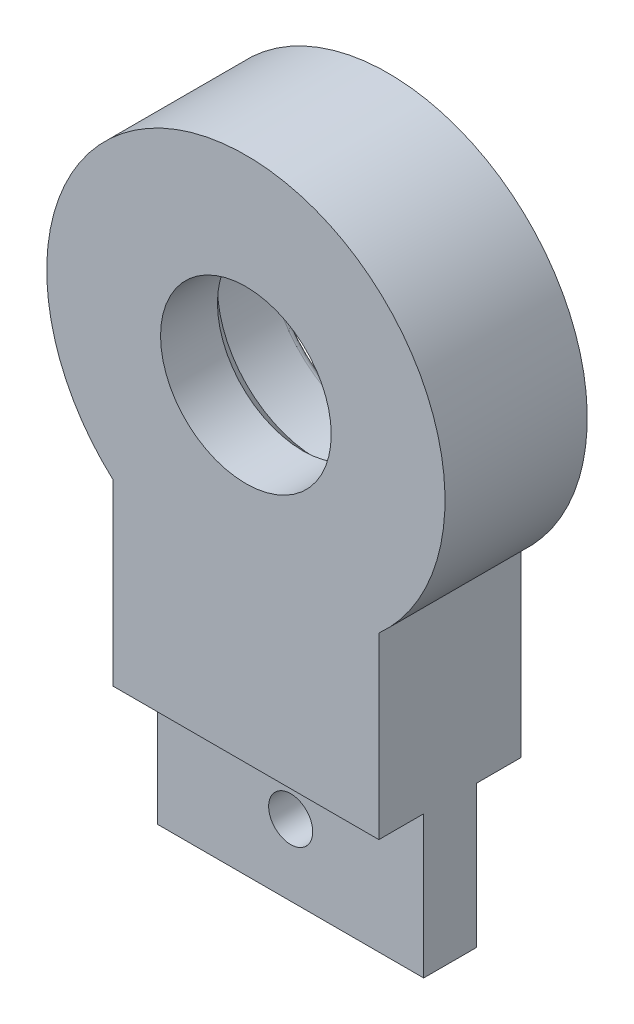
SolidWorks part; units mm, degrees
ref_plane "Front Plane" through (0, 0, 0) normal (0, 0, 1) x (1, 0, 0)
ref_plane "Top Plane" through (0, 0, 0) normal (0, 1, 0) x (1, 0, 0)
ref_plane "Right Plane" through (0, 0, 0) normal (1, 0, 0) x (0, 0, -1)
sketch "Sketch1" plane through (0, 0, 0) normal (0, 0, 1) x (1, 0, 0)
  line L2 (-9.35, -4.9201) -> (-9.35, -17.5)
  line L3 (-9.35, -17.5) -> (9.35, -17.5)
  line L4 (9.35, -4.9201) -> (9.35, -17.5)
  arc A0 (9.35, -4.9201) -> (-9.35, -4.9201) centre (0, 5.5) ccw
  circle A1 centre (0, 5.5) radius 8
  point P0 (0, 0)
  dimension "D3" = 28
  dimension "D4" = 16
  dimension "D2" = 23
  dimension "D1" = 18.7
extrude "Boss-Extrude1" add sketch "Sketch1" along normal blind 10
sketch "Sketch2" plane through (9.35, 0, 0) normal (1, 0, 0) x (0, 0, -1)
  line L0 (-10, -17.5) -> (0, -17.5) construction
  line L1 (-6.85, -7.5) -> (-3.15, -7.5)
  line L2 (-6.85, -7.5) -> (-6.85, -27.5)
  line L3 (-6.85, -27.5) -> (-3.15, -27.5)
  line L4 (-3.15, -7.5) -> (-3.15, -27.5)
  line L5 (-6.85, -7.5) -> (-3.15, -27.5) construction
  line L6 (-6.85, -27.5) -> (-3.15, -7.5) construction
  point P0 (-5, -17.5)
  dimension "D1" = 20
  dimension "D2" = 3.7
extrude "Boss-Extrude2" add sketch "Sketch2" against normal blind 18.7
sketch "Sketch3" plane through (0, 0, 6.85) normal (0, 0, 1) x (1, 0, 0)
  line L0 (-9.35, -27.5) -> (9.35, -27.5) construction
  circle A0 centre (0, -22.5) radius 1.55
  dimension "D1" = 3.1
  dimension "D2" = 5
extrude "Cut-Extrude1" cut sketch "Sketch3" against normal blind 18.7
sketch "Sketch4" plane through (0, 0, 10) normal (0, 0, 1) x (1, 0, 0)
  circle A0 centre (0, 5.5) radius 6
  circle A1 centre (0, 5.5) radius 8
  circle A2 centre (0, 5.5) radius 8 construction
  dimension "D1" = 2
  dimension "D2" = 0
extrude "Boss-Extrude3" add sketch "Sketch4" against normal blind 5
chamfer "Chamfer1" distance 1 angle 45 1 edges at (6, 5.5, 5)
fillet "Fillet1" radius 0.5 1 edges at (8, 5.5, 0)
